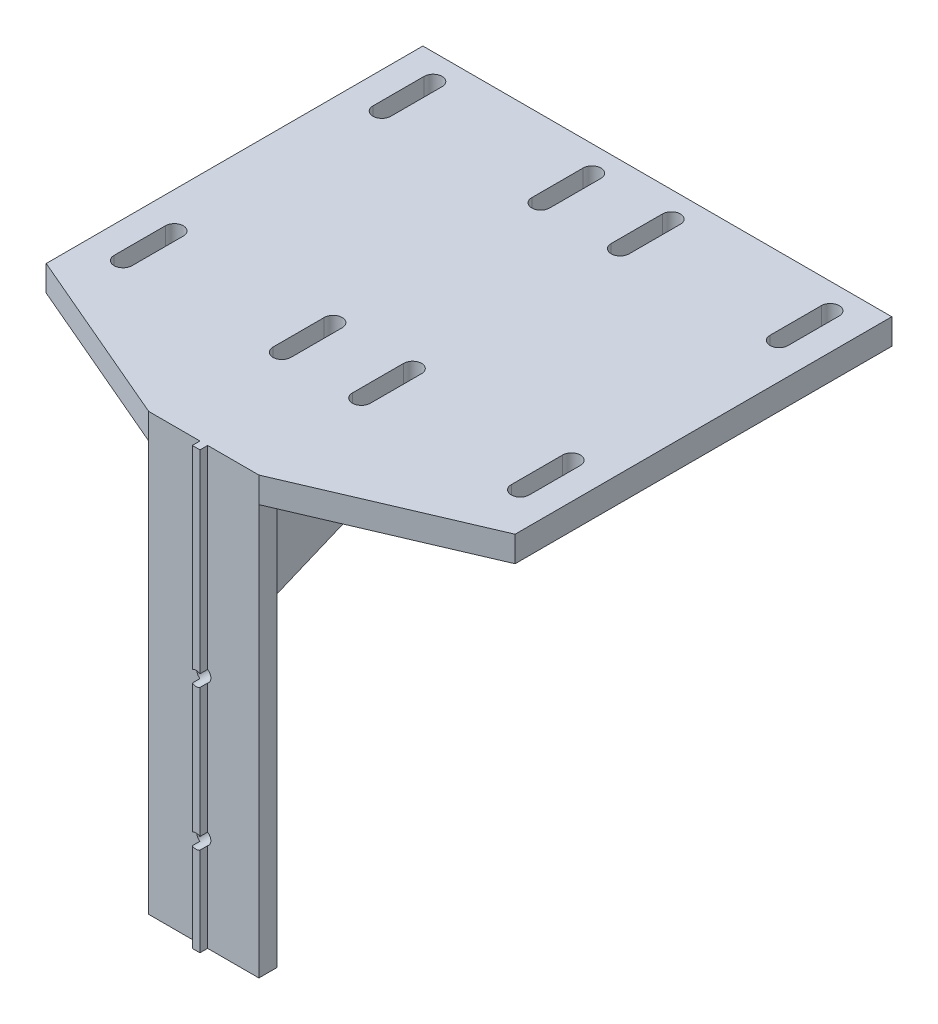
SolidWorks part; units mm, degrees
material "1060 合金"
ref_plane "前视基准面" through (0, 0, 0) normal (0, 0, 1) x (1, 0, 0)
ref_plane "上视基准面" through (0, 0, 0) normal (0, 1, 0) x (1, 0, 0)
ref_plane "右视基准面" through (0, 0, 0) normal (1, 0, 0) x (0, 0, -1)
sketch "草图1" plane through (0, 0, 0) normal (0, 0, 1) x (1, 0, 0)
  line L1 (-21.5, 85) -> (21.5, 85)
  line L2 (-21.5, 85) -> (-21.5, -85)
  line L3 (-21.5, -85) -> (21.5, -85)
  line L4 (21.5, 85) -> (21.5, -85)
  line L5 (-21.5, 85) -> (21.5, -85) construction
  line L6 (-21.5, -85) -> (21.5, 85) construction
  point P0 (0, 0)
  dimension "D1" = 43
  dimension "D2" = 170
extrude "立臂支撑" add sketch "草图1" along normal blind 7
sketch "草图2" plane through (0, 0, 7) normal (0, 0, 1) x (1, 0, 0)
  line L0 (21.5, 85) -> (-21.5, 85) construction
  line L1 (-1.5, 85) -> (1.5, 85)
  line L2 (-1.5, 85) -> (-1.5, -85)
  line L3 (-1.5, -85) -> (1.5, -85)
  line L4 (1.5, 85) -> (1.5, -85)
  line L5 (-21.5, -85) -> (21.5, -85) construction
  line L6 (-21.5, 85) -> (-21.5, -85) construction
  dimension "D1" = 3
  dimension "D2" = 20
extrude "定位突出" add sketch "草图2" along normal blind 3
hole_wizard "M5*2 沉头孔" positions "草图7" profile "草图8" countersink size "M5" standard "ISO" end condition up to next
sketch "草图7" plane through (0, 0, 0) normal (0, 0, -1) x (-1, 0, 0)
  line L0 (-21.5, -85) -> (-21.5, 85) construction
  line L1 (-21.5, 85) -> (21.5, 85) construction
  point P0 (0, 7)
  point P2 (0, -48)
  dimension "D1" = 21.5
  dimension "D2" = 55
  dimension "D3" = 78
sketch "草图8" plane through (0, 7, 0) normal (1, 0, 0) x (0, 1, 0)
  line L0 (0, 0) -> (0, 10)
  line L1 (0, 10) -> (2.75, 10)
  line L2 (2.75, 10) -> (2.75, 2.85)
  line L3 (2.75, 2.85) -> (5.6, 0)
  line L5 (5.6, 0) -> (0, 0)
  line L6 (-2.75, 2.85) -> (-5.6, 0) construction
  line L11 (0, -6.35) -> (0, 107.95) construction
  dimension "通孔孔直径" = 5.5
  dimension "通孔孔深度" = 10
  dimension "近端锥形沉头孔直径" = 11.2
  dimension "近端锥形沉头孔角度" = 90
sketch "草图9" plane through (0, 0, 0) normal (0, 0, -1) x (-1, 0, 0)
  line L0 (-21.5, -85) -> (-21.5, 85) construction
  line L1 (-91.5, 85) -> (91.5, 85)
  line L2 (-91.5, 85) -> (-91.5, 75)
  line L3 (-91.5, 75) -> (91.5, 75)
  line L4 (91.5, 85) -> (91.5, 75)
  line L5 (21.5, 85) -> (21.5, -85) construction
  line L6 (-21.5, 85) -> (21.5, 85) construction
  dimension "D1" = 10
  dimension "D2" = 70
  dimension "D3" = 70
extrude "显微镜平台" add sketch "草图9" along normal blind 170
sketch "草图10" plane through (0, 0, 0) normal (0, 0, 1) x (1, 0, 0)
  line L1 (91.5, 85) -> (-91.5, 85)
  line L2 (91.5, 85) -> (91.5, 75)
  line L3 (91.5, 75) -> (-91.5, 75)
  line L4 (-91.5, 85) -> (-91.5, 75)
extrude "显微镜补充" add sketch "草图10" along normal up to surface (7 mm away) up to face at (6.8125, -10.25, 7)
sketch "草图11" plane through (0, 0, 0) normal (1, 0, 0) x (0, 0, -1)
  line L0 (0, 74.9659) -> (0, 24.9659)
  line L1 (0, 24.9659) -> (120, 74.9659)
  line L2 (120, 74.9659) -> (0, 74.9659)
  dimension "D1" = 50
  dimension "D2" = 120
extrude "凸台-拉伸3" add sketch "草图11" along normal blind 10 and the other way blind 10
sketch "草图12" plane through (0, 85, 0) normal (0, 1, 0) x (1, 0, 0)
  line L0 (-77.5, 160) -> (-77.5, 140) construction
  line L1 (-74, 160) -> (-74, 140)
  line L2 (-81, 160) -> (-81, 140)
  line L3 (-91.5, 170) -> (-91.5, -7) construction
  line L5 (-91.5, 170) -> (91.5, 170) construction
  arc A0 (-74, 160) -> (-81, 160) centre (-77.5, 160) ccw
  arc A1 (-81, 140) -> (-74, 140) centre (-77.5, 140) ccw
  point P2 (-77.5, 150)
  dimension "D1" = 3.5
  dimension "D2" = 14
  dimension "D3" = 10
  dimension "D4" = 10
extrude "切除-拉伸1" cut sketch "草图12" against normal through all
ref_plane "基准面2" through (0, 0, -163.5) normal (0, 0, 1) x (1, 0, 0)
ref_plane "基准面3" through (0, 0, -99.5) normal (0, 0, 1) x (1, 0, 0)
mirror "镜向1" about plane through (0, 0, -99.5) normal (0, 0, 1) of "切除-拉伸1"
ref_plane "基准面4" through (-46.5, 0, 0) normal (-1, 0, 0) x (0, 0, 1)
mirror "镜向2" about plane through (-46.5, 0, 0) normal (-1, 0, 0) of "镜向1", "切除-拉伸1"
sketch "草图13" plane through (0, 85, 0) normal (0, 1, 0) x (1, 0, 0)
  line L0 (-91.5, -7) -> (-21.5, -7)
  line L1 (-1.5, -7) -> (-91.5, -7) construction
  line L2 (-21.5, -7) -> (-91.5, 23)
  line L3 (-91.5, 170) -> (-91.5, -7) construction
  line L4 (-91.5, 23) -> (-91.5, -7)
  dimension "D1" = 70
  dimension "D2" = 30
extrude "切除-拉伸2" cut sketch "草图13" against normal blind 10
mirror "镜向3" about plane through (0, 0, 0) normal (1, 0, 0) of "切除-拉伸2", "镜向2", "切除-拉伸1", "镜向1"
